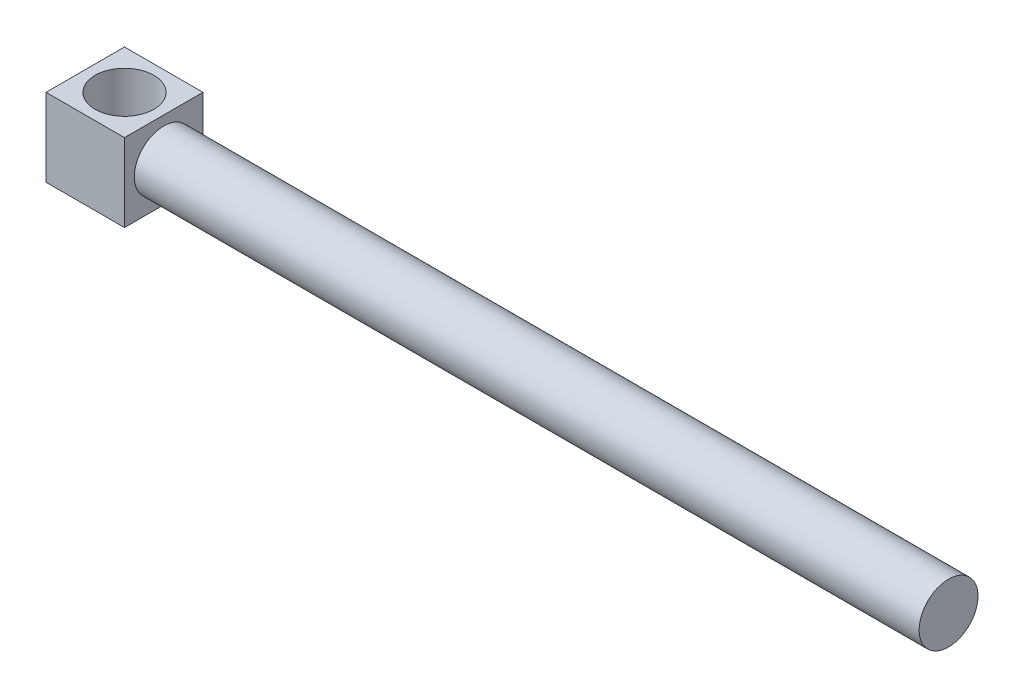
SolidWorks part; units mm, degrees
ref_plane "Front View" through (0, 0, 0) normal (0, 0, 1) x (1, 0, 0)
ref_plane "Upper View" through (0, 0, 0) normal (0, 1, 0) x (1, 0, 0)
ref_plane "Right View" through (0, 0, 0) normal (1, 0, 0) x (0, 0, -1)
sketch "Sketch1" plane through (0, 0, 0) normal (1, 0, 0) x (0, 0, -1)
  line L1 (0, 0) -> (20, 0)
  line L2 (0, 0) -> (0, 19.8521)
  line L3 (0, 19.8521) -> (20, 19.8521)
  line L4 (20, 0) -> (20, 19.8521)
  point P7 (0, 19.8521)
  point P8 (0, 0)
extrude "Boss-Extrude1" add sketch "Sketch1" along normal blind 20 contours L3 L4 L1 L2
sketch "Sketch2" plane through (0, 19.8521, 0) normal (0, 1, 0) x (1, 0, 0)
  circle A0 centre (10, 10) radius 7.5
extrude "Cut-Extrude1" cut sketch "Sketch2" against normal blind 20
sketch "Sketch3" plane through (20, 0, 0) normal (1, 0, 0) x (0, 0, -1)
  circle A0 centre (10, 9.9261) radius 7.5
extrude "Boss-Extrude2" add sketch "Sketch3" along normal blind 200
